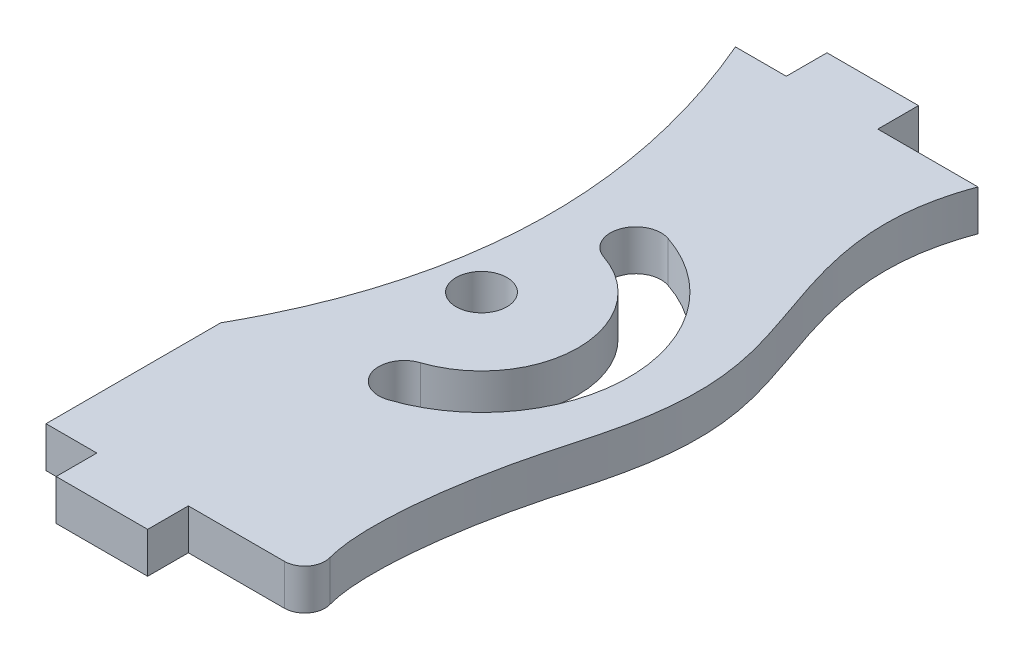
SolidWorks part; units mm, degrees
ref_plane "Alzado" through (0, 0, 0) normal (0, 0, 1) x (1, 0, 0)
ref_plane "Planta" through (0, 0, 0) normal (0, 1, 0) x (1, 0, 0)
ref_plane "Vista lateral" through (0, 0, 0) normal (1, 0, 0) x (0, 0, -1)
sketch "Croquis1" plane through (0, 0, 0) normal (0, 1, 0) x (1, 0, 0)
  line L0 (-29.8355, 18.6892) -> (3.5276, 18.6892) construction
  line L1 (2.715, 0) -> (2.715, 2.0882) construction
  line L3 (-0.3831, 0.651) -> (0.3831, 0.651)
  line L4 (-0.3831, 0.651) -> (-0.3831, -0.651)
  line L5 (-0.3831, -0.651) -> (0.3831, -0.651)
  line L6 (0.3831, 0.651) -> (0.3831, -0.651)
  line L7 (-0.3831, 0.651) -> (0.3831, -0.651) construction
  line L8 (-0.3831, -0.651) -> (0.3831, 0.651) construction
  line L10 (-4.2005, 16.6892) -> (-1.7005, 16.6892)
  line L11 (-1.7005, 16.6892) -> (-1.7005, 18.6892)
  line L12 (-1.7005, 18.6892) -> (2.7995, 18.6892)
  line L13 (2.7995, 18.6892) -> (2.7995, 16.6892)
  line L14 (2.7995, 16.6892) -> (7.7266, 16.6892)
  line L16 (-21.2785, 20.7575) -> (-21.2785, -9.2425) construction
  line L17 (1.8937, -16.3108) -> (6.6151, -16.3108)
  line L18 (1.8937, -18.3108) -> (1.8937, -16.3108)
  line L19 (-2.6063, -18.3108) -> (1.8937, -18.3108)
  line L20 (-2.6063, -16.3108) -> (-2.6063, -18.3108)
  line L21 (-5.1063, -16.3108) -> (-2.6063, -16.3108)
  line L22 (-5.1063, -7.7189) -> (-5.1063, -16.3108)
  circle A0 centre (0, 0) radius 1.25
  arc A3 (4.1833, -4.3012) -> (5.6435, -2.0375) centre (0, 0) ccw
  arc A4 (4.1833, -4.3012) -> (5.6435, -2.0375) centre (0, 0) ccw construction
  arc A10 (6.6151, -16.3108) -> (7.5777, -15.04) centre (6.6151, -15.3108) ccw
  arc A15 (0.6716, -5.9623) -> (6, 0) centre (0, 0) ccw
  arc A17 (1.8924, 5.6937) -> (0.6716, 5.9623) centre (0, 0) ccw
  arc A18 (1.8924, -5.6937) -> (6, 0) centre (0, 0) ccw construction
  arc A19 (2.2867, -6.8799) -> (2.2867, 6.8799) centre (0, 0) ccw
  arc A20 (1.4982, -4.5075) -> (1.4982, 4.5075) centre (0, 0) ccw
  arc A21 (1.4982, -4.5075) -> (2.2867, -6.8799) centre (1.8924, -5.6937) ccw
  arc A22 (2.2867, 6.8799) -> (1.4982, 4.5075) centre (1.8924, 5.6937) ccw
  arc A23 (0.6716, -5.9623) -> (6, 0) centre (0, 0) ccw
  arc A24 (1.8924, 5.6937) -> (0.6716, 5.9623) centre (0, 0) ccw
  spline S0 degree 3 poles (7.5777, -15.04) (7.0091, -13.0184) (7.4797, -8.2818) (9.8371, -0.2699) (9.5069, 5.6257) (5.8998, 11.8316) (7.7266, 16.6892) knots 0.078668 0.078668 0.078668 0.078668 0.337938 0.393993 0.63921 1 1 1 1
  spline S1 degree 2 poles (-4.2005, 16.6892) (1.3277, 3.7559) (-5.1063, -7.7189) knots 0 0 0 1 1 1
  point P12 (6, 0)
  point P15 (4.1833, -4.3012)
  point P26 (-5.2403, 2.9223)
  dimension "D1" = 2.5
  dimension "D3" = 1
  dimension "D4" = 30
  dimension "D2" = 12
  dimension "D5" = 2
  dimension "D6" = 4.5
  dimension "D7" = 2.5
  dimension "D8" = 2
  dimension "D9" = 2.5
  dimension "D10" = 4.5
extrude "Saliente-Extruir1" add sketch "Croquis1" along normal blind 2
